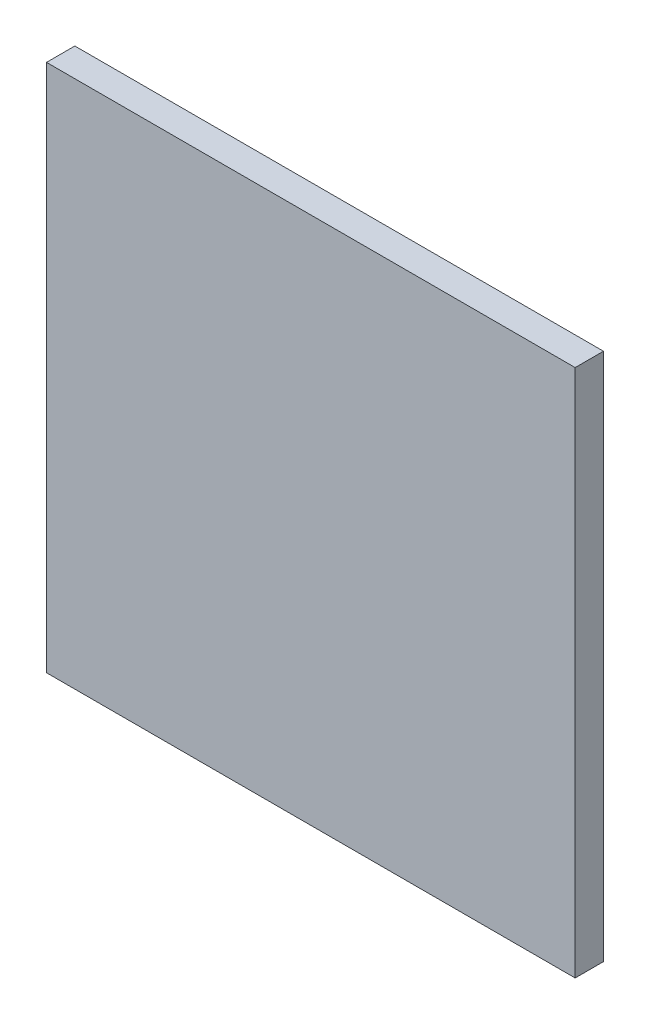
SolidWorks part; units mm, degrees
ref_plane "Front Plane" through (0, 0, 0) normal (0, 0, 1) x (1, 0, 0)
ref_plane "Top Plane" through (0, 0, 0) normal (0, 1, 0) x (1, 0, 0)
ref_plane "Right Plane" through (0, 0, 0) normal (1, 0, 0) x (0, 0, -1)
sketch "Sketch1" plane through (0, 0, 0) normal (0, 0, 1) x (1, 0, 0)
  line L4 (-108.69, -94) -> (-108.69, -66)
  line L5 (-108.69, -66) -> (-136.69, -66)
  line L6 (-136.69, -66) -> (-136.69, -94)
  line L7 (-136.69, -94) -> (-108.69, -94)
  line L8 (-108.69, -94) -> (-108.69, -66)
  line L9 (-108.69, -66) -> (-136.69, -66)
  line L10 (-136.69, -66) -> (-136.69, -94)
  line L11 (-136.69, -94) -> (-108.69, -94)
  dimension "D1" = 0
extrude "Extrude1" add sketch "Sketch1" along normal blind 1.5
